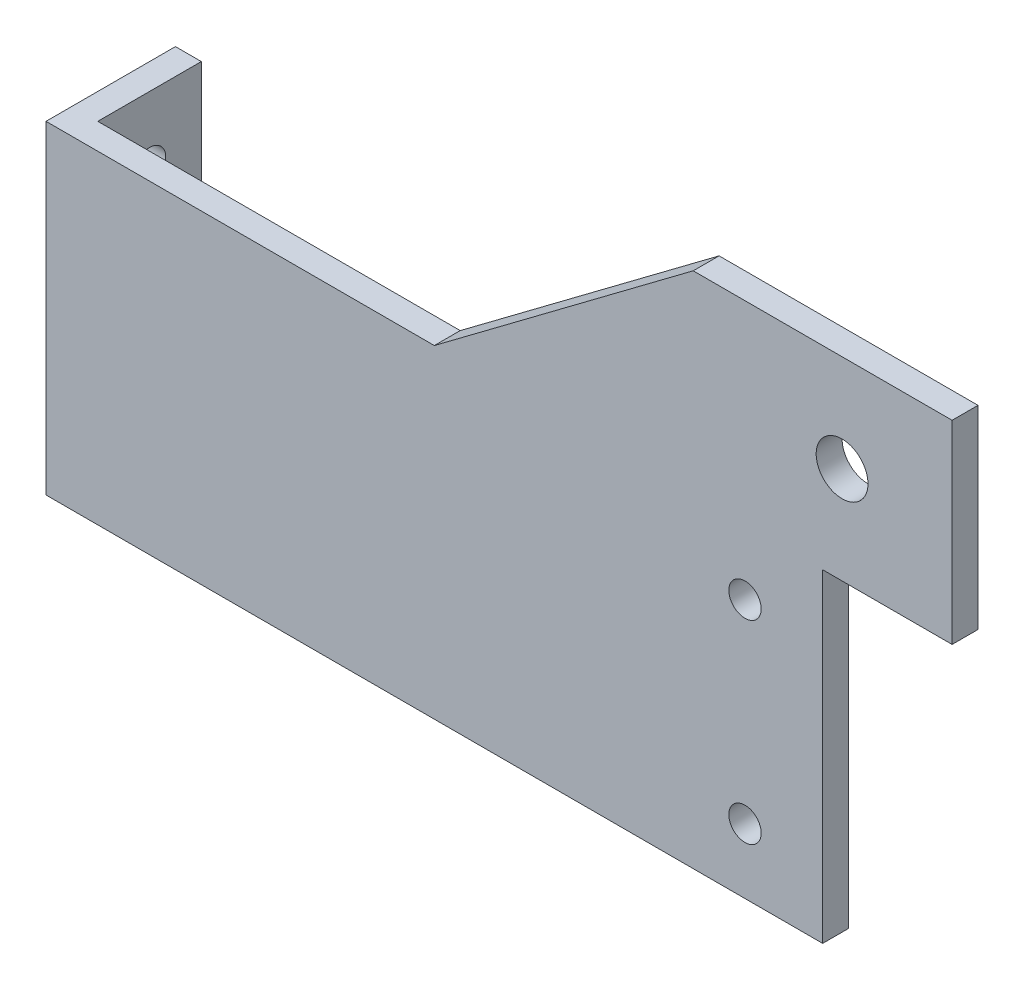
SolidWorks part; units mm, degrees
ref_plane "Спереди" through (0, 0, 0) normal (0, 0, 1) x (1, 0, 0)
ref_plane "Сверху" through (0, 0, 0) normal (0, 1, 0) x (1, 0, 0)
ref_plane "Справа" through (0, 0, 0) normal (1, 0, 0) x (0, 0, -1)
sketch "Эскиз1" plane through (0, 0, 0) normal (0, 1, 0) x (1, 0, 0)
  line L1 (0, 0) -> (140, 0)
  line L2 (0, 0) -> (0, 4)
  line L3 (4, 4) -> (140, 4)
  line L4 (140, 0) -> (140, 4)
  line L6 (0, 4) -> (0, 20)
  line L7 (0, 20) -> (4, 20)
  line L8 (4, 4) -> (4, 20)
  dimension "D1" = 140
  dimension "D2" = 4
  dimension "D3" = 20
  dimension "D4" = 4
extrude "Бобышка-Вытянуть1" add sketch "Эскиз1" along normal blind 80
sketch "Эскиз2" plane through (0, 0, 0) normal (-1, 0, 0) x (0, 0, 1)
  line L0 (-12, 44.9311) -> (-12, 11.555) construction
  line L2 (-20, 0) -> (0, 0) construction
  line L3 (0, 80) -> (0, 0) construction
  circle A0 centre (-12, 40) radius 2.5
  circle A1 centre (-12, 10) radius 2.5
  dimension "D2" = 5
  dimension "D3" = 5
  dimension "D1" = 12
  dimension "D4" = 30
  dimension "D5" = 10
extrude "Вырез-Вытянуть1" cut sketch "Эскиз2" against normal blind 10
sketch "Эскиз3" plane through (0, 0, 0) normal (0, 0, 1) x (1, 0, 0)
  line L0 (108, 46.6766) -> (108, 6.7064) construction
  line L2 (0, 0) -> (140, 0) construction
  line L3 (92.0296, 65) -> (67.349, 65) construction
  line L4 (0, 80) -> (0, 0) construction
  circle A0 centre (108, 40) radius 2.5
  circle A1 centre (108, 10) radius 2.5
  circle A2 centre (123, 65) radius 4
  dimension "D2" = 5
  dimension "D3" = 5
  dimension "D6" = 8
  dimension "D1" = 108
  dimension "D4" = 30
  dimension "D5" = 10
  dimension "D7" = 25
  dimension "D8" = 15
extrude "Вырез-Вытянуть2" cut sketch "Эскиз3" against normal blind 10
sketch "Эскиз4" plane through (0, 0, 0) normal (0, 0, 1) x (1, 0, 0)
  line L0 (60, 80) -> (60, 0) construction
  line L1 (0, 80) -> (140, 80) construction
  line L3 (0, 50) -> (60, 50)
  line L4 (0, 80) -> (0, 0) construction
  line L5 (0, 0) -> (140, 0) construction
  line L6 (60, 50) -> (100, 80)
  line L7 (0, 50) -> (0, 80)
  line L8 (100, 80) -> (0, 80)
  dimension "D1" = 40
  dimension "D2" = 50
extrude "Вырез-Вытянуть3" cut sketch "Эскиз4" against normal blind 30
sketch "Эскиз5" plane through (0, 0, 0) normal (0, 0, 1) x (1, 0, 0)
  line L0 (120, 0) -> (120, 50)
  line L1 (0, 0) -> (140, 0) construction
  line L2 (120, 50) -> (140, 50)
  line L3 (140, 80) -> (140, 0) construction
  line L4 (140, 50) -> (140, 0)
  line L5 (140, 0) -> (120, 0)
  line L6 (0, 50) -> (0, 0) construction
  dimension "D1" = 120
  dimension "D2" = 50
extrude "Вырез-Вытянуть4" cut sketch "Эскиз5" against normal blind 10
